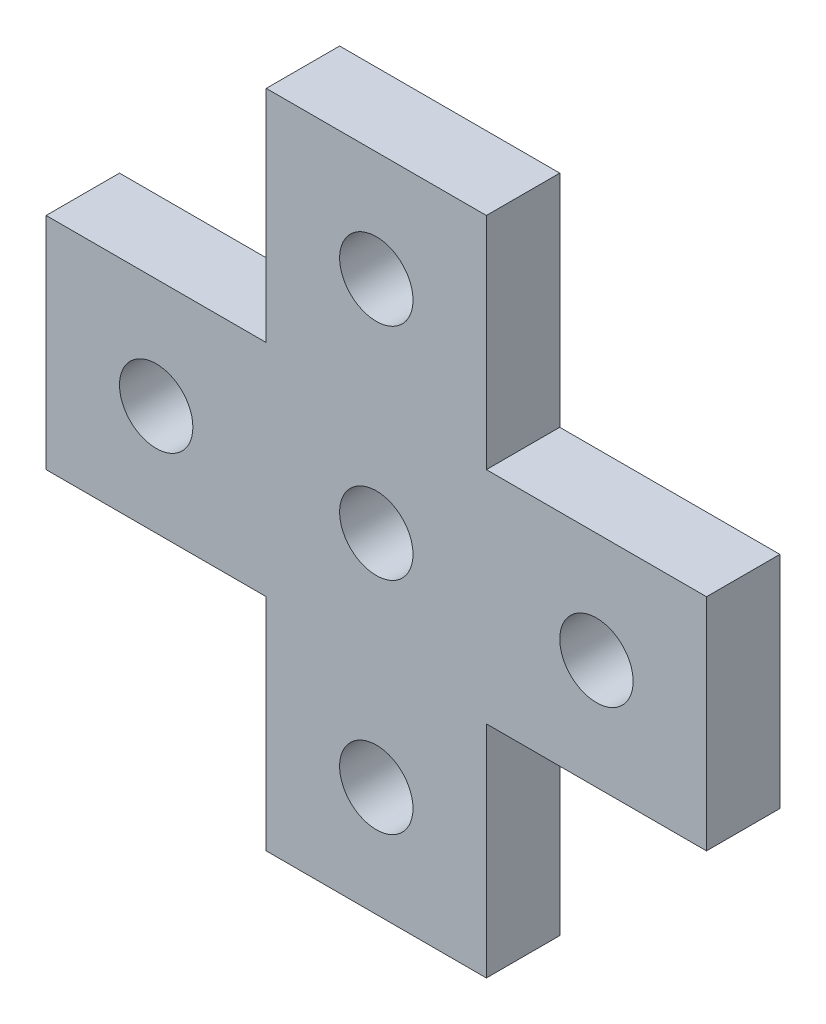
SolidWorks part; units mm, degrees
ref_plane "Alzado" through (0, 0, 0) normal (0, 0, 1) x (1, 0, 0)
ref_plane "Planta" through (0, 0, 0) normal (0, 1, 0) x (1, 0, 0)
ref_plane "Vista lateral" through (0, 0, 0) normal (1, 0, 0) x (0, 0, -1)
sketch "Model" plane through (0, 0, 0) normal (0, 0, 1) x (1, 0, 0)
  line L0 (213.2508, 165.9285) -> (213.2508, 174.9285)
  line L1 (204.2508, 174.9285) -> (204.2508, 165.9285)
  line L2 (222.2508, 165.9285) -> (213.2508, 165.9285)
  line L3 (213.2508, 156.9285) -> (222.2508, 156.9285)
  line L4 (213.2508, 147.9285) -> (213.2508, 156.9285)
  line L5 (204.2508, 165.9285) -> (195.2508, 165.9285)
  line L6 (204.2508, 156.9285) -> (204.2508, 147.9285)
  line L7 (195.2508, 156.9285) -> (204.2508, 156.9285)
  line L8 (213.2508, 147.9285) -> (204.2508, 147.9285)
  line L9 (213.2508, 174.9285) -> (204.2508, 174.9285)
  line L10 (222.2508, 165.9285) -> (222.2508, 156.9285)
  line L11 (195.2508, 165.9285) -> (195.2508, 156.9285)
  circle A0 centre (208.7508, 152.4285) radius 1.5
  circle A1 centre (208.7508, 161.4285) radius 1.5
  circle A2 centre (208.7508, 170.4285) radius 1.5
  circle A3 centre (199.7508, 161.4285) radius 1.5
  circle A4 centre (217.7508, 161.4285) radius 1.5
extrude "Saliente-Extruir1" add sketch "Model" along normal blind 3
